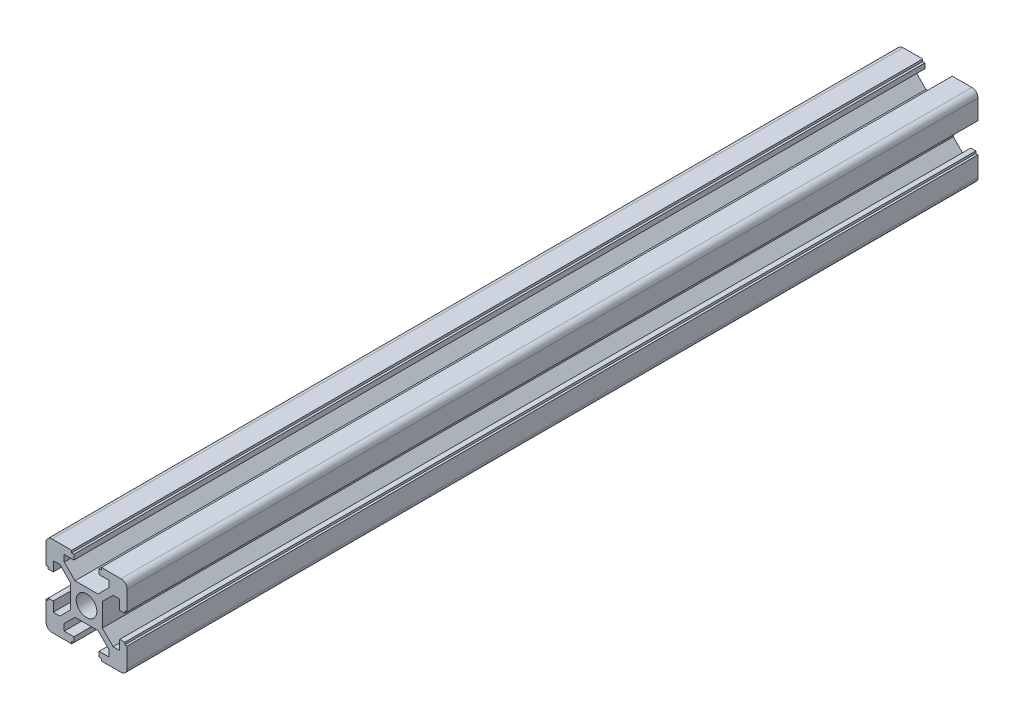
SolidWorks part; units mm, degrees
material "6063-T5"
ref_plane "前视基准面" through (0, 0, 0) normal (0, 0, 1) x (1, 0, 0)
ref_plane "上视基准面" through (0, 0, 0) normal (0, 1, 0) x (1, 0, 0)
ref_plane "右视基准面" through (0, 0, 0) normal (1, 0, 0) x (0, 0, -1)
sketch "草图2" plane through (0, 0, 0) normal (0, 0, 1) x (1, 0, 0)
  line L0 (-3.9, 2.8393) -> (-6.5607, 5.5)
  line L1 (-2.8393, 3.9) -> (2.8393, 3.9)
  line L2 (-3.9, 2.8393) -> (-3.9, -2.8393)
  line L3 (-2.8393, -3.9) -> (2.8393, -3.9)
  line L4 (3.9, 2.8393) -> (3.9, -2.8393)
  line L5 (-3.9, 3.9) -> (3.9, -3.9) construction
  line L6 (-3.9, -3.9) -> (3.9, 3.9) construction
  line L7 (-2.8393, 3.9) -> (-5.5, 6.5607)
  line L8 (-5.5, 6.5607) -> (-5.5, 8.2)
  line L9 (-5.5, 8.2) -> (-3.1, 8.2)
  line L10 (-3.1, 8.2) -> (-3.1, 9.45)
  line L11 (-3.1, 9.45) -> (-3.65, 9.45)
  line L12 (-3.65, 9.45) -> (-3.65, 10)
  line L13 (-3.65, 10) -> (-8.5, 10)
  line L14 (-6.5607, 5.5) -> (-8.2, 5.5)
  line L15 (-10, 3.65) -> (-10, 8.5)
  line L16 (-9.45, 3.65) -> (-10, 3.65)
  line L17 (-9.45, 3.1) -> (-9.45, 3.65)
  line L18 (-8.2, 3.1) -> (-9.45, 3.1)
  line L19 (-8.2, 5.5) -> (-8.2, 3.1)
  line L20 (2.8393, 3.9) -> (5.5, 6.5607)
  line L21 (3.9, 2.8393) -> (6.5607, 5.5)
  line L22 (6.5607, 5.5) -> (8.2, 5.5)
  line L23 (8.2, 5.5) -> (8.2, 3.1)
  line L24 (8.2, 3.1) -> (9.45, 3.1)
  line L25 (9.45, 3.1) -> (9.45, 3.65)
  line L26 (9.45, 3.65) -> (10, 3.65)
  line L27 (10, 3.65) -> (10, 8.5)
  line L28 (5.5, 6.5607) -> (5.5, 8.2)
  line L29 (3.65, 10) -> (8.5, 10)
  line L30 (3.65, 9.45) -> (3.65, 10)
  line L31 (3.1, 9.45) -> (3.65, 9.45)
  line L32 (3.1, 8.2) -> (3.1, 9.45)
  line L33 (5.5, 8.2) -> (3.1, 8.2)
  line L34 (3.9, -2.8393) -> (6.5607, -5.5)
  line L35 (2.8393, -3.9) -> (5.5, -6.5607)
  line L36 (5.5, -6.5607) -> (5.5, -8.2)
  line L37 (5.5, -8.2) -> (3.1, -8.2)
  line L38 (3.1, -8.2) -> (3.1, -9.45)
  line L39 (3.1, -9.45) -> (3.65, -9.45)
  line L40 (3.65, -9.45) -> (3.65, -10)
  line L41 (3.65, -10) -> (8.5, -10)
  line L42 (6.5607, -5.5) -> (8.2, -5.5)
  line L43 (10, -3.65) -> (10, -8.5)
  line L44 (9.45, -3.65) -> (10, -3.65)
  line L45 (9.45, -3.1) -> (9.45, -3.65)
  line L46 (8.2, -3.1) -> (9.45, -3.1)
  line L47 (8.2, -5.5) -> (8.2, -3.1)
  line L48 (-2.8393, -3.9) -> (-5.5, -6.5607)
  line L49 (-3.9, -2.8393) -> (-6.5607, -5.5)
  line L50 (-6.5607, -5.5) -> (-8.2, -5.5)
  line L51 (-8.2, -5.5) -> (-8.2, -3.1)
  line L52 (-8.2, -3.1) -> (-9.45, -3.1)
  line L53 (-9.45, -3.1) -> (-9.45, -3.65)
  line L54 (-9.45, -3.65) -> (-10, -3.65)
  line L55 (-10, -3.65) -> (-10, -8.5)
  line L56 (-5.5, -6.5607) -> (-5.5, -8.2)
  line L57 (-3.65, -10) -> (-8.5, -10)
  line L58 (-3.65, -9.45) -> (-3.65, -10)
  line L59 (-3.1, -9.45) -> (-3.65, -9.45)
  line L60 (-3.1, -8.2) -> (-3.1, -9.45)
  line L61 (-5.5, -8.2) -> (-3.1, -8.2)
  circle A0 centre (0, 0) radius 2.55
  arc A1 (-8.5, 10) -> (-10, 8.5) centre (-8.5, 8.5) ccw
  arc A2 (10, 8.5) -> (8.5, 10) centre (8.5, 8.5) ccw
  arc A3 (8.5, -10) -> (10, -8.5) centre (8.5, -8.5) ccw
  arc A4 (-10, -8.5) -> (-8.5, -10) centre (-8.5, -8.5) ccw
  point P25 (-10, 10)
  point P79 (0, 0)
  dimension "D1" = 5.1
  dimension "D9" = 1.5
  dimension "D2" = 7.8
  dimension "D3" = 1.5
  dimension "D4" = 10
  dimension "D5" = 3.1
  dimension "D6" = 0.55
  dimension "D7" = 1.8
  dimension "D8" = 5.5
  dimension "D11" = 3.9
  dimension "D10" = 4
extrude "凸台-拉伸1" add sketch "草图2" along normal blind 210
